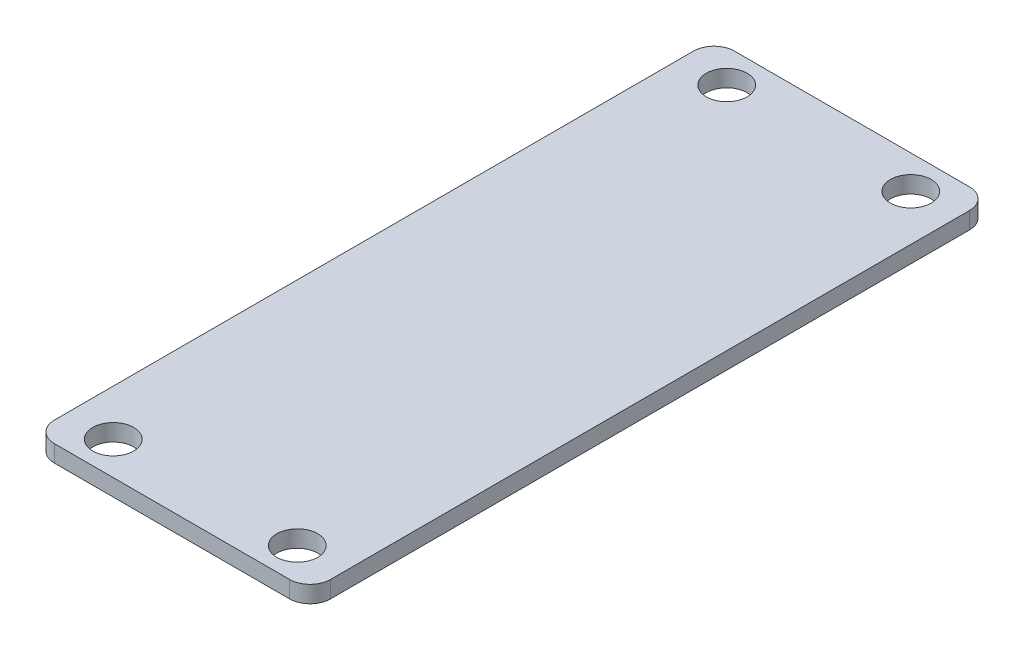
SolidWorks part; units mm, degrees
ref_plane "Front Plane" through (0, 0, 0) normal (0, 0, 1) x (1, 0, 0)
ref_plane "Top Plane" through (0, 0, 0) normal (0, 1, 0) x (1, 0, 0)
ref_plane "Right Plane" through (0, 0, 0) normal (1, 0, 0) x (0, 0, -1)
sketch "Sketch1" plane through (0, 0, 0) normal (0, 1, 0) x (1, 0, 0)
  line L1 (13.5, -33.25) -> (-13.5, -33.25)
  line L2 (13.5, -33.25) -> (13.5, 33.25)
  line L3 (13.5, 33.25) -> (-13.5, 33.25)
  line L4 (-13.5, -33.25) -> (-13.5, 33.25)
  line L5 (13.5, -33.25) -> (-13.5, 33.25) construction
  line L6 (13.5, 33.25) -> (-13.5, -33.25) construction
  point P0 (0, 0)
  dimension "D1" = 27
  dimension "D2" = 66.5
extrude "Boss-Extrude1" add sketch "Sketch1" along normal blind 1.65
fillet "Fillet1" radius 2 4 edges at (13.5, 0.825, -33.25) (-13.5, 0.825, -33.25) (-13.5, 0.825, 33.25) (13.5, 0.825, 33.25)
sketch "Sketch2" plane through (0, 1.65, 0) normal (0, 1, 0) x (1, 0, 0)
  line L1 (9, -30) -> (-9, -30) construction
  line L2 (9, -30) -> (9, 30) construction
  line L3 (9, 30) -> (-9, 30) construction
  line L4 (-9, -30) -> (-9, 30) construction
  line L5 (9, -30) -> (-9, 30) construction
  line L6 (9, 30) -> (-9, -30) construction
  circle A0 centre (-9, 30) radius 2
  circle A1 centre (9, 30) radius 2
  circle A2 centre (9, -30) radius 2
  circle A3 centre (-9, -30) radius 2
  point P0 (0, 0)
  dimension "D3" = 4
  dimension "D1" = 60
  dimension "D2" = 18
extrude "Cut-Extrude1" cut sketch "Sketch2" against normal through all
